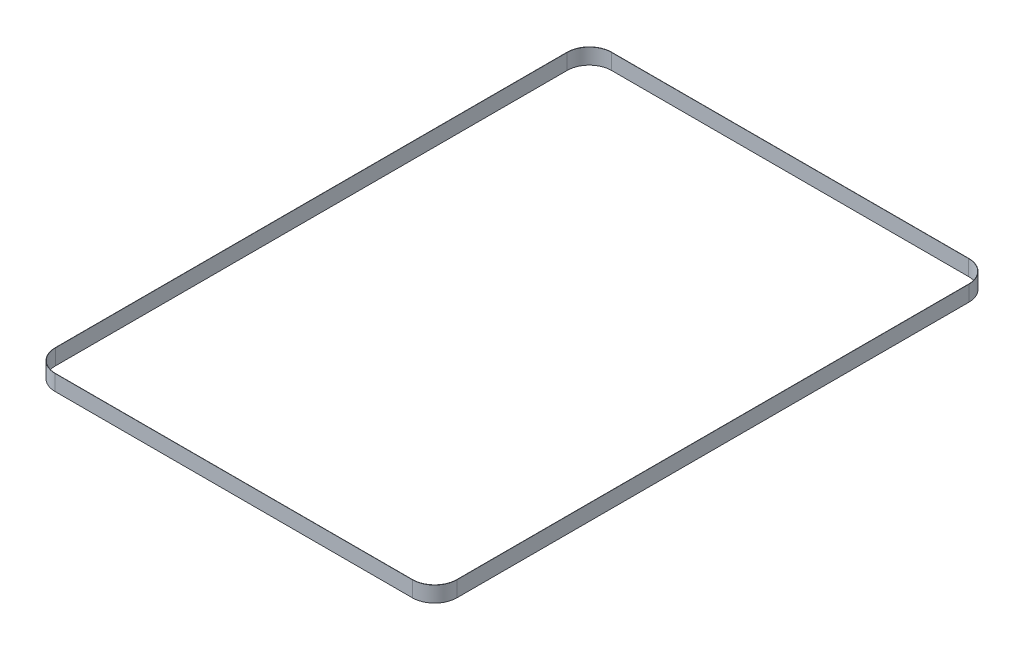
SolidWorks part; units mm, degrees
ref_plane "Front Plane" through (0, 0, 0) normal (0, 0, 1) x (1, 0, 0)
ref_plane "Top Plane" through (0, 0, 0) normal (0, 1, 0) x (1, 0, 0)
ref_plane "Right Plane" through (0, 0, 0) normal (1, 0, 0) x (0, 0, -1)
sketch "Esquisse" plane through (0, 0, 0) normal (0, 1, 0) x (1, 0, 0)
  line L0 (-0.1, 10) -> (-0.1, 238.6)
  line L1 (-10, 0) -> (-169.5, 0)
  line L2 (0, 10) -> (0, 238.6)
  line L3 (-10, 248.6) -> (-169.5, 248.6)
  line L4 (-179.5, 10) -> (-179.5, 238.6)
  line L5 (-10, 248.5) -> (-169.5, 248.5)
  line L6 (-179.4, 10) -> (-179.4, 238.6)
  line L7 (-10, 0.1) -> (-169.5, 0.1)
  arc A0 (-10, 0) -> (0, 10) centre (-10, 10) ccw
  arc A1 (-169.5, 0) -> (-179.5, 10) centre (-169.5, 10) cw
  arc A2 (-169.5, 248.6) -> (-179.5, 238.6) centre (-169.5, 238.6) ccw
  arc A3 (0, 238.6) -> (-10, 248.6) centre (-10, 238.6) ccw
  arc A4 (-0.1, 238.6) -> (-10, 248.5) centre (-10, 238.6) ccw
  arc A5 (-169.5, 248.5) -> (-179.4, 238.6) centre (-169.5, 238.6) ccw
  arc A6 (-169.5, 0.1) -> (-179.4, 10) centre (-169.5, 10) cw
  arc A7 (-10, 0.1) -> (-0.1, 10) centre (-10, 10) ccw
  point P7 (0, 0)
  point P10 (-179.5, 0)
  point P13 (-179.5, 248.6)
  point P16 (0, 248.6)
  dimension "D3" = 10
  dimension "D1" = 179.5
  dimension "D2" = 248.6
extrude "Boss.-Extru.1" add sketch "Esquisse" along normal blind 7
